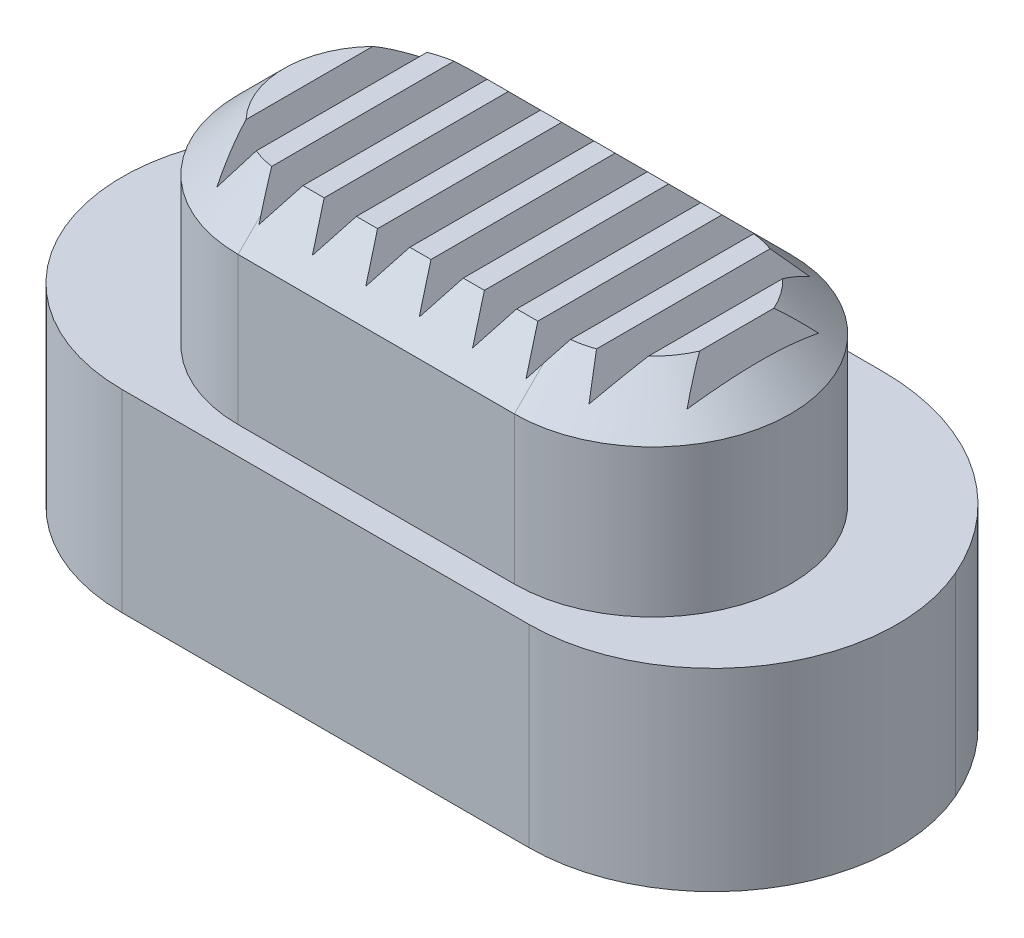
SolidWorks part; units mm, degrees
ref_plane "前视基准面" through (0, 0, 0) normal (0, 0, 1) x (1, 0, 0)
ref_plane "上视基准面" through (0, 0, 0) normal (0, 1, 0) x (1, 0, 0)
ref_plane "右视基准面" through (0, 0, 0) normal (1, 0, 0) x (0, 0, -1)
other "Configuration Table"
sketch "草图1" plane through (0, 0, 0) normal (0, 1, 0) x (1, 0, 0)
  line L0 (0, 0) -> (7, 0) construction
  line L1 (0, 5) -> (7, 5)
  line L2 (0, -5) -> (7, -5)
  arc A0 (0, 5) -> (0, -5) centre (0, 0) ccw
  arc A1 (7, -5) -> (7, 5) centre (7, 0) ccw
  point P3 (3.5, 0)
  dimension "D1" = 5
  dimension "D2" = 7
extrude "凸台-拉伸1" add sketch "草图1" along normal blind 4.2
sketch "草图3" plane through (0, 0, 0) normal (0, -1, 0) x (1, 0, 0)
  circle A0 centre (0, 0) radius 1.75
  dimension "D1" = 3.5
extrude "切除-拉伸1" cut sketch "草图3" against normal up to next
sketch "草图4" plane through (0, 4.2, 0) normal (0, 1, 0) x (1, 0, 0)
  line L0 (1, 0) -> (7, 0) construction
  line L1 (1, 3) -> (7, 3)
  line L2 (1, -3) -> (7, -3)
  arc A0 (1, 3) -> (1, -3) centre (1, 0) ccw
  arc A1 (7, -3) -> (7, 3) centre (7, 0) ccw
  arc A2 (0, 5) -> (0, -5) centre (0, 0) ccw construction
  arc A3 (7, -5) -> (7, 5) centre (7, 0) ccw construction
  point P3 (4, 0)
  dimension "D1" = 3
  dimension "D2" = 1
extrude "凸台-拉伸2" add sketch "草图4" along normal blind 4.2
chamfer "倒角1" distance 1 angle 45 4 edges at (4, 8.4, -3) (-2, 8.4, 0) (10, 8.4, 0) (4, 8.4, 3)
sketch "草图5" plane through (0, 4.2, 0) normal (0, 1, 0) x (1, 0, 0)
  line L0 (7, -3) -> (1, -3) construction
  line L1 (-3.4699, -3.6) -> (10.4699, -3.6)
  line L2 (-3.4699, -3.6) -> (-3.4699, -5)
  line L3 (-3.4699, -5) -> (10.4699, -5)
  line L4 (10.4699, -3.6) -> (10.4699, -5)
  line L5 (-3.4699, -3.6) -> (10.4699, -5) construction
  line L6 (-3.4699, -5) -> (10.4699, -3.6) construction
  line L7 (0, -5) -> (7, -5) construction
  arc A0 (0, 5) -> (0, -5) centre (0, 0) ccw construction
  arc A1 (7, -5) -> (7, 5) centre (7, 0) ccw construction
  point P4 (3.5, -4.3)
  dimension "D1" = 0.6
extrude "切除-拉伸2" cut sketch "草图5" against normal up to next
fillet "圆角1" radius 4 2 edges at (-3.4699, 2.1, 3.6) (10.4699, 2.1, 3.6)
sketch "草图6" plane through (0, 0, 3.6) normal (0, 0, 1) x (1, 0, 0)
  line L0 (-0.45, 8.4) -> (-0.1, 7.7938)
  line L1 (1, 8.4) -> (-1, 8.4) construction
  line L2 (-0.1, 7.7938) -> (0.25, 8.4)
  line L3 (0.25, 8.4) -> (-0.45, 8.4)
  line L4 (-0.1, 7.7938) -> (-0.1, 8.4) construction
  line L5 (-2, 7.4) -> (-2, 4.2) construction
  line L6 (1.41, 8.4) -> (0.71, 8.4)
  line L7 (0.71, 8.4) -> (1.06, 7.7938)
  line L8 (1.06, 7.7938) -> (1.41, 8.4)
  line L9 (2.57, 8.4) -> (1.87, 8.4)
  line L10 (1.87, 8.4) -> (2.22, 7.7938)
  line L11 (2.22, 7.7938) -> (2.57, 8.4)
  line L12 (3.73, 8.4) -> (3.03, 8.4)
  line L13 (3.03, 8.4) -> (3.38, 7.7938)
  line L14 (3.38, 7.7938) -> (3.73, 8.4)
  line L15 (4.89, 8.4) -> (4.19, 8.4)
  line L16 (4.19, 8.4) -> (4.54, 7.7938)
  line L17 (4.54, 7.7938) -> (4.89, 8.4)
  line L18 (6.05, 8.4) -> (5.35, 8.4)
  line L19 (5.35, 8.4) -> (5.7, 7.7938)
  line L20 (5.7, 7.7938) -> (6.05, 8.4)
  line L21 (7.21, 8.4) -> (6.51, 8.4)
  line L22 (6.51, 8.4) -> (6.86, 7.7938)
  line L23 (6.86, 7.7938) -> (7.21, 8.4)
  line L24 (8.37, 8.4) -> (7.67, 8.4)
  line L25 (7.67, 8.4) -> (8.02, 7.7938)
  line L26 (8.02, 7.7938) -> (8.37, 8.4)
  line L27 (9.53, 8.4) -> (8.83, 8.4)
  line L28 (8.83, 8.4) -> (9.18, 7.7938)
  line L29 (9.18, 7.7938) -> (9.53, 8.4)
  line L33 (0.25, 8.4) -> (1.41, 8.4) construction
  line L34 (10.69, 8.4) -> (9.99, 8.4) [skipped]
  line L35 (9.99, 8.4) -> (10.34, 7.7938) [skipped]
  line L36 (10.34, 7.7938) -> (10.69, 8.4) [skipped]
  dimension "D1" = 0.7
  dimension "D2" = 1.9
  dimension "D4" = 1.16
  dimension "D3" = 10
extrude "切除-拉伸3" cut sketch "草图6" against normal up to next
